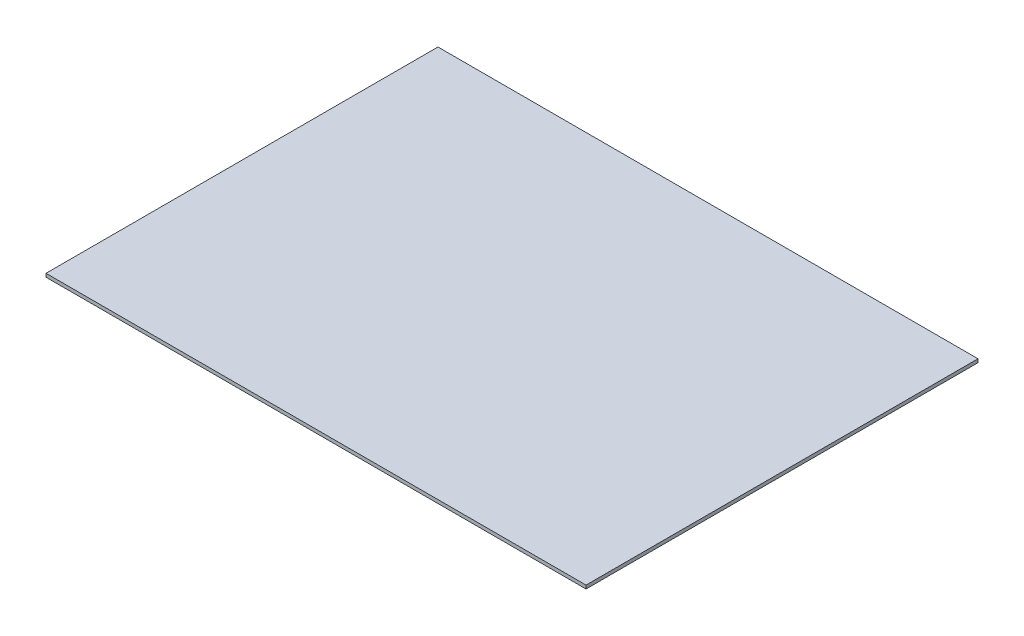
SolidWorks part; units mm, degrees
material "Verre"
ref_plane "Plan de face" through (0, 0, 0) normal (0, 0, 1) x (1, 0, 0)
ref_plane "Plan de dessus" through (0, 0, 0) normal (0, 1, 0) x (1, 0, 0)
ref_plane "Plan de droite" through (0, 0, 0) normal (1, 0, 0) x (0, 0, -1)
sketch "Esquisse1" plane through (0, 0, 0) normal (0, 1, 0) x (1, 0, 0)
  line L1 (-315.5, -229) -> (315.5, -229)
  line L2 (-315.5, -229) -> (-315.5, 229)
  line L3 (-315.5, 229) -> (315.5, 229)
  line L4 (315.5, -229) -> (315.5, 229)
  line L5 (-315.5, -229) -> (315.5, 229) construction
  line L6 (-315.5, 229) -> (315.5, -229) construction
  point P0 (0, 0)
  dimension "D1" = 458
  dimension "D2" = 631
extrude "Boss.-Extru.1" add sketch "Esquisse1" along normal blind 4
